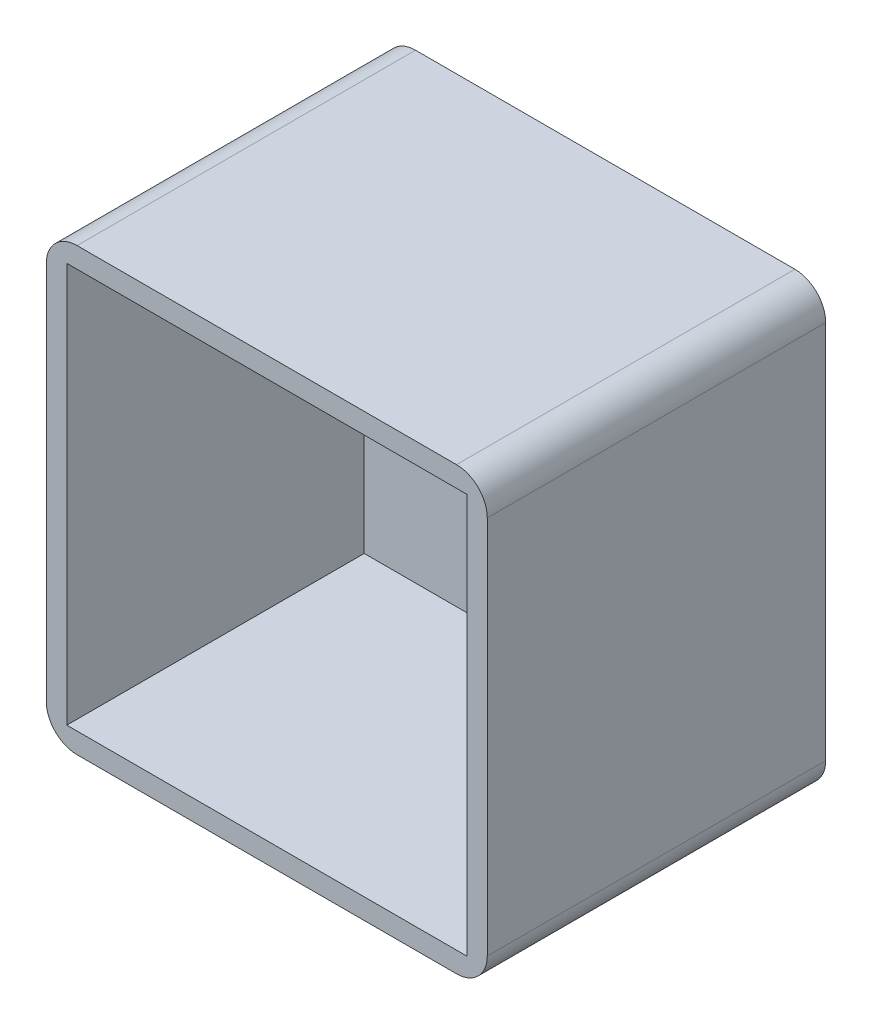
SolidWorks part; units mm, degrees
ref_plane "Front Plane" through (0, 0, 0) normal (1, 0, 0) x (0, 1, 0)
ref_plane "Top Plane" through (0, 0, 0) normal (0, 0, 1) x (0, 1, 0)
ref_plane "Right Plane" through (0, 0, 0) normal (0, 1, 0) x (-1, 0, 0)
sketch "Sketch1" plane through (0, 0, 0) normal (0, 0, 1) x (0, 1, 0)
  line L1 (0, 0) -> (-39, 0)
  line L2 (0, 0) -> (0, 39)
  line L3 (0, 39) -> (-39, 39)
  line L4 (-39, 0) -> (-39, 39)
  line L5 (-41, 41) -> (2, 41)
  line L6 (-41, 41) -> (-41, -2)
  line L7 (-41, -2) -> (2, -2)
  line L8 (2, 41) -> (2, -2)
  dimension "D1" = 39
  dimension "D2" = 39
  dimension "D3" = 2
  dimension "D4" = 2
  dimension "D5" = 2
  dimension "D6" = 2
  dimension "D7" = 43
extrude "Boss-Extrude1" add sketch "Sketch1" along normal blind 45 contours L6 L7 L8 L5
sketch "Sketch3" plane through (0, 0, 45) normal (0, 0, 1) x (1, 0, 0)
  line L0 (-3, -13) -> (-3, -25) construction
  line L1 (-39, 0) -> (0, 0)
  line L2 (-39, 0) -> (-39, -39.3012)
  line L3 (-39, -39.3012) -> (0, -39.3012)
  line L4 (0, 0) -> (0, -39.3012)
  line L5 (0, -13) -> (0, -25)
  line L6 (-6, -13) -> (-6, -25)
  line L7 (-36, -13) -> (-36, -25) construction
  line L8 (-33, -13) -> (-33, -25)
  line L9 (-39, -13) -> (-39, -25)
  circle A0 centre (-20, -19) radius 7.25
  arc A1 (0, -13) -> (-6, -13) centre (-3, -13) ccw
  arc A2 (-6, -25) -> (0, -25) centre (-3, -25) ccw
  arc A3 (-33, -13) -> (-39, -13) centre (-36, -13) ccw
  arc A4 (-39, -25) -> (-33, -25) centre (-36, -25) ccw
  circle A5 centre (-20, -3.5068) radius 3
  point P12 (-3, -19)
  point P20 (-36, -19)
  dimension "D7" = 14.5
  dimension "D8" = 12
  dimension "D14" = 6
  dimension "D16" = 3
  dimension "D17" = 3
  dimension "D9" = 12
  dimension "D1" = 2
  dimension "D2" = 1.6988
  dimension "D3" = 2
  dimension "D4" = 2
  dimension "D5" = 19
  dimension "D6" = 19
  dimension "D10" = 3
  dimension "D11" = 3
  dimension "D12" = 19
  dimension "D13" = 19
  dimension "D15" = 19
extrude "Cut-Extrude4" cut sketch "Sketch3" against normal blind 38 contours A5 | A0 | L6 A2 L5 A1 | L8 A4 L9 A3
sketch "Sketch6" plane through (0, 0, 45) normal (0, 0, 1) x (1, 0, 0)
  line L1 (-41, 2) -> (2, 2)
  line L2 (-41, 2) -> (-41, -41)
  line L3 (-41, -41) -> (2, -41)
  line L4 (2, 2) -> (2, -41)
  line L12 (-39, 0) -> (-39, -39)
  line L13 (-39, -39) -> (0, -39)
  line L14 (0, -39) -> (0, 0)
  line L15 (0, 0) -> (-39, 0)
  line L16 (-39, 0) -> (-39, -39)
  line L17 (-39, -39) -> (0, -39)
  line L18 (0, -39) -> (0, 0)
  line L19 (0, 0) -> (-39, 0)
  point P6 (0, 0)
  point P7 (0, 0)
  dimension "D1" = 2
extrude "Cut-Extrude5" cut sketch "Sketch6" against normal blind 29 contours L19 L16 L17 L18
sketch "Sketch7" plane through (0, 0, 0) normal (0, 0, -1) x (1, 0, 0)
  line L1 (-29.2126, 9.8159) -> (-10.8126, 9.8159)
  line L2 (-29.2126, 9.8159) -> (-29.2126, 28.2159)
  line L3 (-29.2126, 28.2159) -> (-10.8126, 28.2159)
  line L4 (-10.8126, 9.8159) -> (-10.8126, 28.2159)
  line L5 (-29.2126, 9.8159) -> (-10.8126, 28.2159) construction
  line L6 (-29.2126, 28.2159) -> (-10.8126, 9.8159) construction
  line L7 (-41, 41) -> (2, 41)
  line L8 (-41, 41) -> (-41, -2)
  line L9 (-41, -2) -> (2, -2)
  line L10 (2, 41) -> (2, -2)
  circle A0 centre (-20.0126, 19.0159) radius 7.0001
  point P12 (-41, 41)
  dimension "D1" = 18.4
  dimension "D2" = 18.4
extrude "Cut-Extrude8" cut sketch "Sketch7" against normal blind 12
fillet "Fillet2" radius 5 4 edges at (-29.2126, -28.2159, 6) (-29.2126, -9.8159, 6) (-10.8126, -9.8159, 6) (-10.8126, -28.2159, 6)
fillet "Fillet3" radius 3 4 edges at (2, 2, 28.5) (-41, 2, 28.5) (-41, -41, 28.5) (2, -41, 28.5)
sketch "Sketch10" plane through (0, 0, 0) normal (0, 0, -1) x (1, 0, 0)
  line L1 (-30.0162, 28.4596) -> (-9.7811, 28.4596)
  line L2 (-30.0162, 28.4596) -> (-30.0162, 9.1357)
  line L3 (-30.0162, 9.1357) -> (-9.7811, 9.1357)
  line L4 (-9.7811, 28.4596) -> (-9.7811, 9.1357)
extrude "Cut-Extrude9" cut sketch "Sketch10" against normal blind 7
